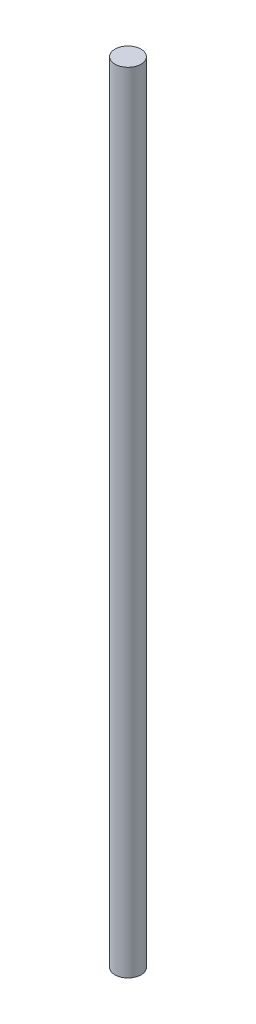
SolidWorks part; units mm, degrees
ref_plane "Front Plane" through (0, 0, 0) normal (0, 0, 1) x (1, 0, 0)
ref_plane "Top Plane" through (0, 0, 0) normal (0, 1, 0) x (1, 0, 0)
ref_plane "Right Plane" through (0, 0, 0) normal (1, 0, 0) x (0, 0, -1)
sketch "Sketch1" plane through (0, 0, 0) normal (0, 1, 0) x (1, 0, 0)
  circle A0 centre (0, 0) radius 2
  dimension "D1" = 4
extrude "Boss-Extrude1" add sketch "Sketch1" along normal mid plane 121
